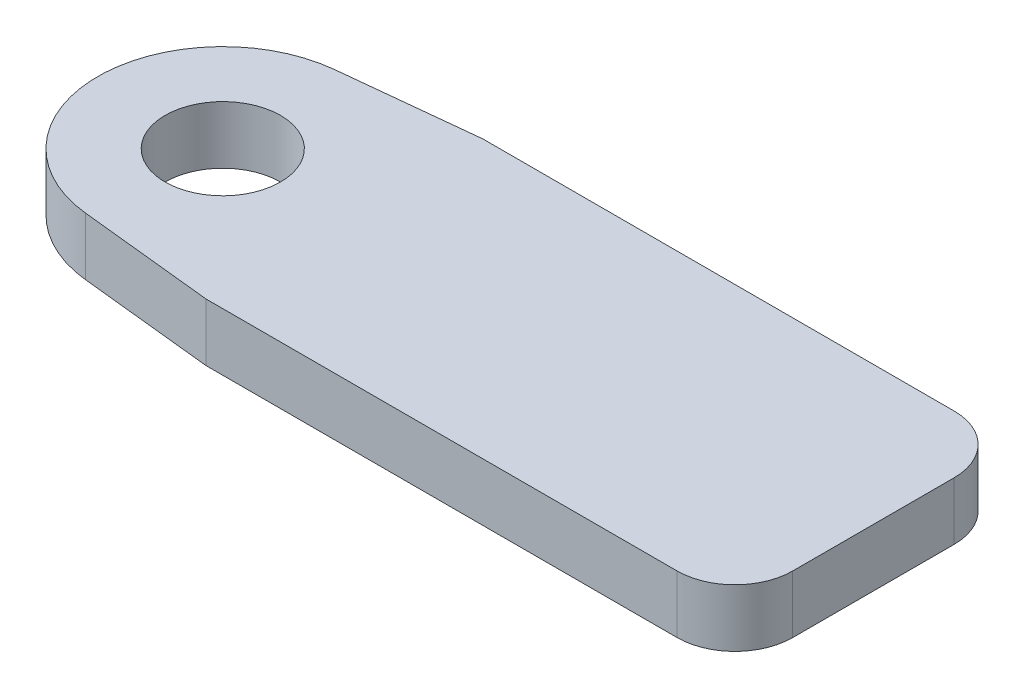
SolidWorks part; units mm, degrees
ref_plane "Front Plane" through (0, 0, 0) normal (0, 0, 1) x (1, 0, 0)
ref_plane "Top Plane" through (0, 0, 0) normal (0, 1, 0) x (1, 0, 0)
ref_plane "Right Plane" through (0, 0, 0) normal (1, 0, 0) x (0, 0, -1)
sketch "Sketch1" plane through (0, 0, 0) normal (0, 1, 0) x (1, 0, 0)
  line L0 (-0.1725, 1.642) -> (1.6055, 1.8288)
  line L1 (-0.1725, -1.642) -> (1.6055, -1.8288)
  line L2 (0, 0) -> (1.6055, 0) construction
  line L3 (1.6055, 1.8288) -> (7.8285, 1.8288)
  line L4 (8.5905, 1.0668) -> (8.5905, -1.0668)
  line L5 (7.8285, -1.8288) -> (1.6055, -1.8288)
  arc A0 (-0.1725, 1.642) -> (-0.1725, -1.642) centre (0, 0) ccw
  circle A1 centre (0, 0) radius 0.762
  arc A2 (8.5905, -1.0668) -> (7.8285, -1.8288) centre (7.8285, -1.0668) cw
  arc A3 (7.8285, 1.8288) -> (8.5905, 1.0668) centre (7.8285, 1.0668) cw
  point P14 (8.5905, 1.8288)
  dimension "D1" = 3.302
  dimension "D5" = 1.524
  dimension "D6" = 0.762
  dimension "D2" = 3.6576
  dimension "D3" = 1.778
  dimension "D4" = 6.985
extrude "Boss-Extrude1" add sketch "Sketch1" along normal mid plane 0.762
